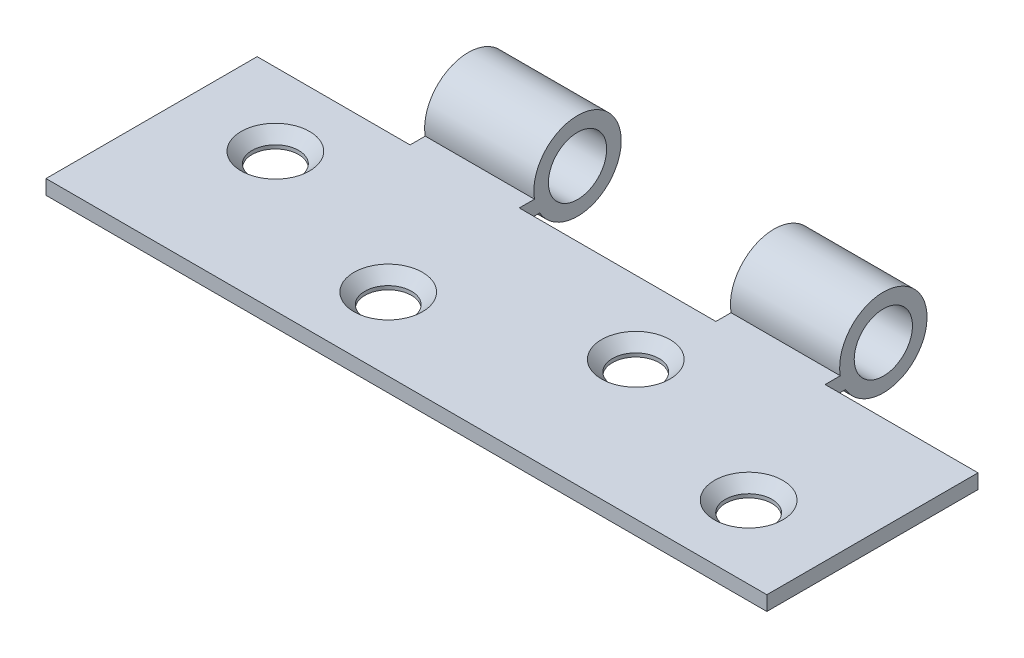
SolidWorks part; units mm, degrees
ref_plane "Front" through (0, 0, 0) normal (0, 0, 1) x (1, 0, 0)
ref_plane "Top" through (0, 0, 0) normal (0, 1, 0) x (1, 0, 0)
ref_plane "Right" through (0, 0, 0) normal (1, 0, 0) x (0, 0, -1)
sketch "草图1" plane through (0, 0, 0) normal (1, 0, 0) x (0, 0, -1)
  circle A0 centre (0, 0) radius 4
  circle A1 centre (0, 0) radius 6
  dimension "D1" = 12
  dimension "D2" = 8
extrude "凸台-拉伸1" add sketch "草图1" along normal blind 99
sketch "草图2" plane through (0, 0, 0) normal (0, 0, 1) x (1, 0, 0)
  line L0 (0, -1) -> (0, -3)
  line L1 (99, -6) -> (99, 6) construction
  line L2 (0, -1) -> (99, -1)
  line L3 (0, 6) -> (0, -6) construction
  line L4 (99, -1) -> (99, -3)
  line L5 (99, -3) -> (0, -3)
  dimension "D1" = 2
  dimension "D2" = 1
extrude "凸台-拉伸2" add sketch "草图2" along normal blind 37
sketch "草图3" plane through (0, 0, 0) normal (-1, 0, 0) x (0, 0, 1)
  circle A0 centre (0, 0) radius 4
extrude "切除-拉伸1" cut sketch "草图3" against normal through all
sketch "草图7" plane through (0, -3, 0) normal (0, -1, 0) x (1, 0, 0)
  line L0 (0, 37) -> (0, 5.9161) construction
  line L1 (99, 37) -> (0, 37) construction
  circle A8 centre (12.5, 18) radius 3.2
  circle A9 centre (37, 27) radius 3.2
  circle A10 centre (62, 18) radius 3.2
  circle A11 centre (86.5, 27) radius 3.2
  dimension "D2" = 6.4
  dimension "D3" = 6.4
  dimension "D4" = 6.4
  dimension "D5" = 6.4
  dimension "D6" = 19
  dimension "D7" = 10
  dimension "D8" = 37
  dimension "D9" = 19
  dimension "D10" = 62
  dimension "D11" = 10
  dimension "D12" = 86.5
  dimension "D1" = 12.5
extrude "切除-拉伸8" cut sketch "草图7" against normal blind 37
sketch "草图8" plane through (0, -1, 0) normal (0, 1, 0) x (1, 0, 0)
  line L0 (0, 6) -> (21, 6)
  line L1 (99, 6) -> (0, 6) construction
  line L2 (21, -8) -> (0, -8)
  line L3 (0, -37) -> (0, -5.9161) construction
  line L4 (0, -8) -> (0, 6)
  line L5 (21, 6) -> (21, -8)
  line L6 (36, 6) -> (36, -8)
  line L8 (99, 6) -> (78, 6)
  line L9 (99, -8) -> (99, 6)
  line L10 (78, -8) -> (99, -8)
  line L11 (78, 6) -> (78, -8)
  line L12 (99, 6) -> (0, 6) construction
  line L13 (36, -8) -> (63, -8)
  line L14 (63, -8) -> (63, 6)
  line L15 (99, 6) -> (0, 6) construction
  line L16 (63, 6) -> (36, 6)
  dimension "D1" = 14
  dimension "D2" = 21
  dimension "D3" = 14
  dimension "D4" = 27
  dimension "D5" = 36
  dimension "D6" = 21
  dimension "D8" = 14
extrude "切除-拉伸9" cut sketch "草图8" against normal through all both and the other way through all
chamfer "倒角2" distance 1.5 angle 45 4 edges at (86.5, -1, 23.8) (62, -1, 14.8) (37, -1, 23.8) (12.5, -1, 14.8)
